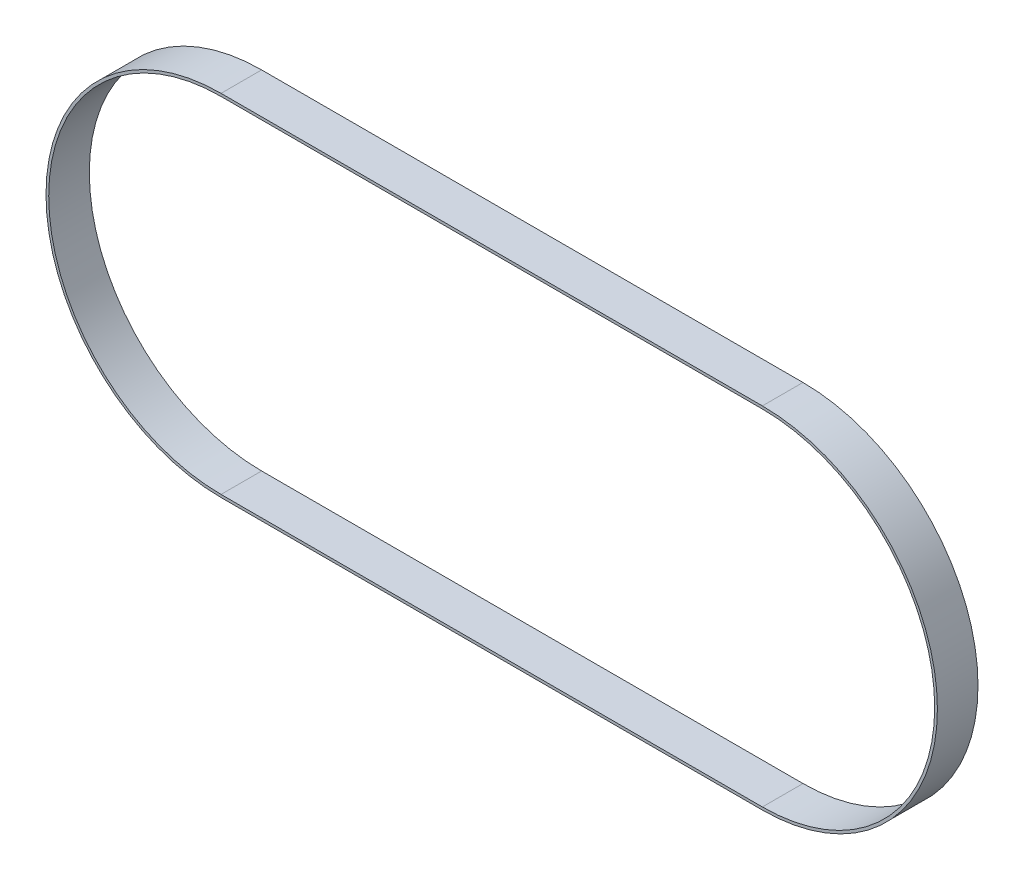
SolidWorks part; units mm, degrees
material "Rubber"
ref_plane "Front Plane" through (0, 0, 0) normal (0, 0, 1) x (1, 0, 0)
ref_plane "Top Plane" through (0, 0, 0) normal (0, 1, 0) x (1, 0, 0)
ref_plane "Right Plane" through (0, 0, 0) normal (1, 0, 0) x (0, 0, -1)
sketch "Sketch1" plane through (0, 0, 0) normal (0, 0, 1) x (1, 0, 0)
  line L0 (-100, 0) -> (100, 0) construction
  line L1 (-100, 63.662) -> (100, 63.662)
  line L2 (-100, -63.662) -> (100, -63.662)
  line L3 (-100, 64.662) -> (100, 64.662)
  line L4 (-100, -64.662) -> (100, -64.662)
  arc A0 (-100, 63.662) -> (-100, -63.662) centre (-100, 0) ccw
  arc A1 (100, -63.662) -> (100, 63.662) centre (100, 0) ccw
  arc A2 (100, -64.662) -> (100, 64.662) centre (100, 0) ccw
  arc A3 (-100, 64.662) -> (-100, -64.662) centre (-100, 0) ccw
  point P2 (0, 0)
  dimension "D1" = 200
  dimension "D2" = 63.662
  dimension "D3" = 1
extrude "Boss-Extrude1" add sketch "Sketch1" along normal blind 15 contours A0 L2 A1 L1
